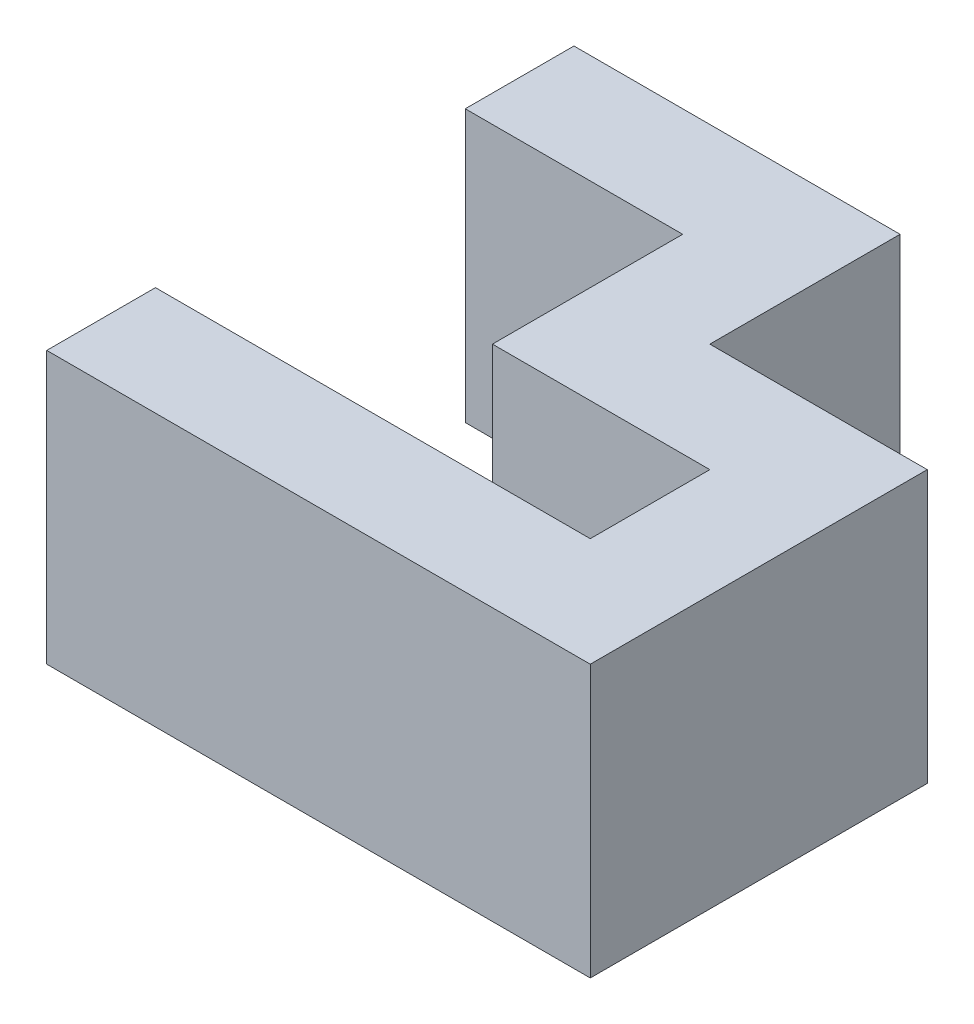
SolidWorks part; units mm, degrees
ref_plane "前视" through (0, 0, 0) normal (0, 0, 1) x (1, 0, 0)
ref_plane "上视" through (0, 0, 0) normal (0, 1, 0) x (1, 0, 0)
ref_plane "右视" through (0, 0, 0) normal (1, 0, 0) x (0, 0, -1)
sketch "Sketch1" plane through (0, 0, 0) normal (0, 1, 0) x (1, 0, 0)
  line L0 (0, 0) -> (10, 0)
  line L1 (10, 0) -> (10, 6.2)
  line L2 (10, 6.2) -> (6, 6.2)
  line L3 (6, 6.2) -> (6, 9.7)
  line L4 (6, 9.7) -> (0, 9.7)
  line L5 (0, 9.7) -> (0, 7.7)
  line L6 (0, 7.7) -> (4, 7.7)
  line L7 (4, 7.7) -> (4, 4.2)
  line L8 (4, 4.2) -> (8, 4.2)
  line L9 (8, 4.2) -> (8, 2)
  line L10 (8, 2) -> (0, 2)
  line L11 (0, 2) -> (0, 0)
  dimension "D1" = 2.2
  dimension "D2" = 2
  dimension "D3" = 2
  dimension "D4" = 3.5
  dimension "D5" = 2
  dimension "D6" = 2
  dimension "D7" = 2
  dimension "D8" = 10
  dimension "D9" = 4
extrude "Boss-Extrude1" add sketch "Sketch1" along normal blind 5
